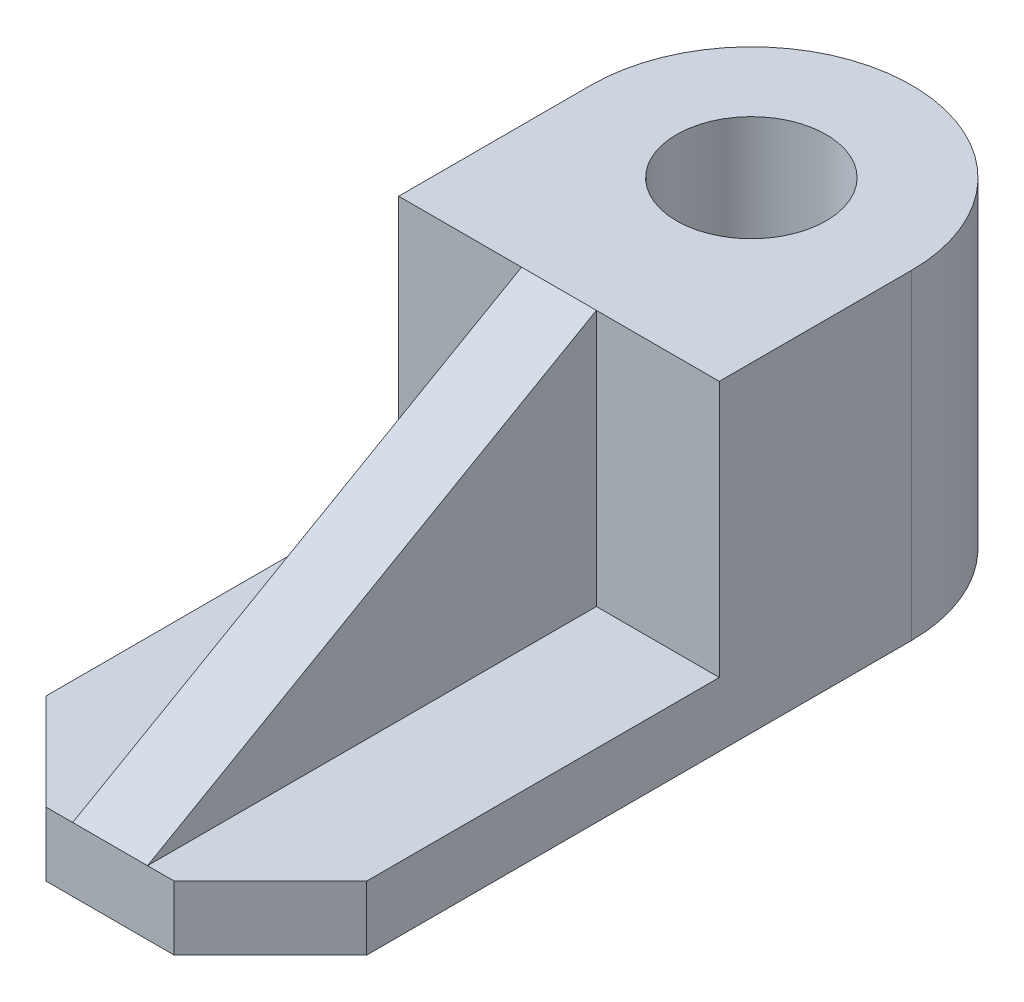
SolidWorks part; units mm, degrees
ref_plane "Front Plane" through (0, 0, 0) normal (0, 0, 1) x (1, 0, 0)
ref_plane "Top Plane" through (0, 0, 0) normal (0, 1, 0) x (1, 0, 0)
ref_plane "Right Plane" through (0, 0, 0) normal (1, 0, 0) x (0, 0, -1)
sketch "Sketch1" plane through (0, 0, 0) normal (0, 1, 0) x (1, 0, 0)
  line L5 (0, 0) -> (30, 0)
  line L6 (0, 0) -> (0, 18)
  line L8 (30, 0) -> (30, 18)
  arc A0 (30, 18) -> (0, 18) centre (15, 18) ccw
  circle A1 centre (15, 18) radius 7
  dimension "D3" = 14
  dimension "D4" = 15
  dimension "D1" = 18
  dimension "D2" = 30
extrude "Boss-Extrude2" add sketch "Sketch1" along normal blind 30
sketch "Sketch3" plane through (0, 0, 0) normal (0, -1, 0) x (-1, 0, 0)
  line L0 (-21, -42) -> (-30, -33)
  line L1 (-21, -42) -> (-9, -42)
  line L2 (-30, -33) -> (-30, 0)
  line L3 (-30, 0) -> (0, 0)
  line L4 (0, -33) -> (0, 0)
  line L5 (-9, -42) -> (0, -33)
  point P0 (-30, -42)
  point P3 (0, -42)
  dimension "D1" = 42
  dimension "D2" = 30
  dimension "D3" = 60
extrude "Boss-Extrude4" add sketch "Sketch3" against normal blind 6
ref_plane "Plane1" through (15, 0, 0) normal (-1, 0, 0) x (0, 0, 1)
sketch "Sketch5" plane through (15, 0, 0) normal (-1, 0, 0) x (0, 0, 1)
  line L0 (0, 30) -> (42, 6)
rib "Rib3" sketch "Sketch5" sketch "Sketch5" thickness 7 extrusion direction parallel to sketch draft on no parameters "D1"=7
